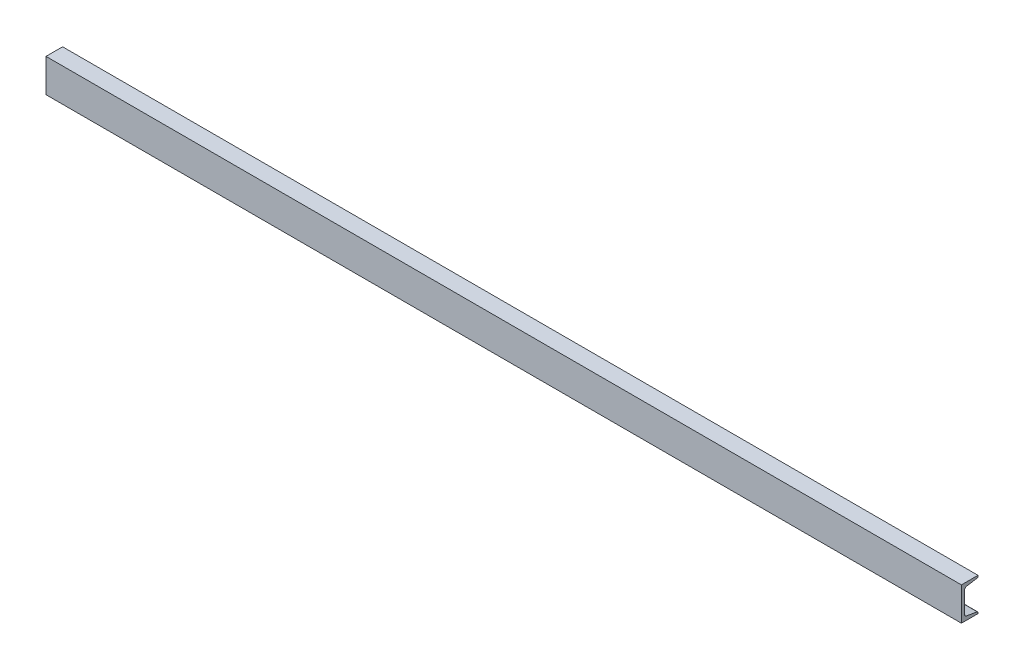
SolidWorks part; units mm, degrees
ref_plane "Alzado" through (0, 0, 0) normal (0, 0, 1) x (1, 0, 0)
ref_plane "Planta" through (0, 0, 0) normal (0, 1, 0) x (1, 0, 0)
ref_plane "Vista lateral" through (0, 0, 0) normal (1, 0, 0) x (0, 0, -1)
sketch "Croquis1" plane through (0, 0, 0) normal (0, 1, 0) x (1, 0, 0)
  line L0 (0, 0) -> (2100, 0)
  dimension "D1" = 2100
other "Canal c 3 X 5(1)"
ref_plane "Plano1" through (0, 0, 0) normal (1, 0, 0) x (0, 0, -1)
sketch "Sketch12" plane through (0, 0, 0) normal (1, 0, 0) x (0, 0, -1)
  line L0 (0, -38.1) -> (0, 38.1)
  line L1 (0, 38.1) -> (38.0492, 38.1)
  line L2 (0, -38.1) -> (38.0492, -38.1)
  line L5 (31.75, -31.1658) -> (6.35, -31.1658) construction
  line L6 (0, 0) -> (6.5532, 0) construction
  line L12 (6.5532, 22.7314) -> (6.5532, -22.7314)
  line L15 (38.0492, 38.1) -> (38.0492, 35.9423)
  line L16 (38.0492, -38.1) -> (38.0492, -35.9423)
  line L17 (12.2837, 29.4961) -> (35.9268, 33.4369)
  line L18 (12.2837, -29.4961) -> (35.9268, -33.4369)
  arc A9 (6.5532, -22.7314) -> (12.2837, -29.4961) centre (13.4112, -22.7314) ccw
  arc A10 (6.5532, 22.7314) -> (12.2837, 29.4961) centre (13.4112, 22.7314) cw
  arc A11 (38.0492, 35.9423) -> (35.9268, 33.4369) centre (35.5092, 35.9423) cw
  arc A12 (38.0492, -35.9423) -> (35.9268, -33.4369) centre (35.5092, -35.9423) ccw
  point P4 (38.0492, 33.7907)
  point P5 (38.0492, -33.7907)
  point P6 (3.2766, 0)
  point P7 (19.0246, 38.1)
  point P12 (19.0246, -38.1)
  point P13 (0, 0)
  dimension "RI" = 6.858
  dimension "D2" = 9.463
  dimension "RA" = 2.54
  dimension "Depth" = 76.2
  dimension "BF" = 38.0492
  dimension "TW" = 6.5532
  dimension "flange" = 2.1577
  dimension "TF" = 6.9342
